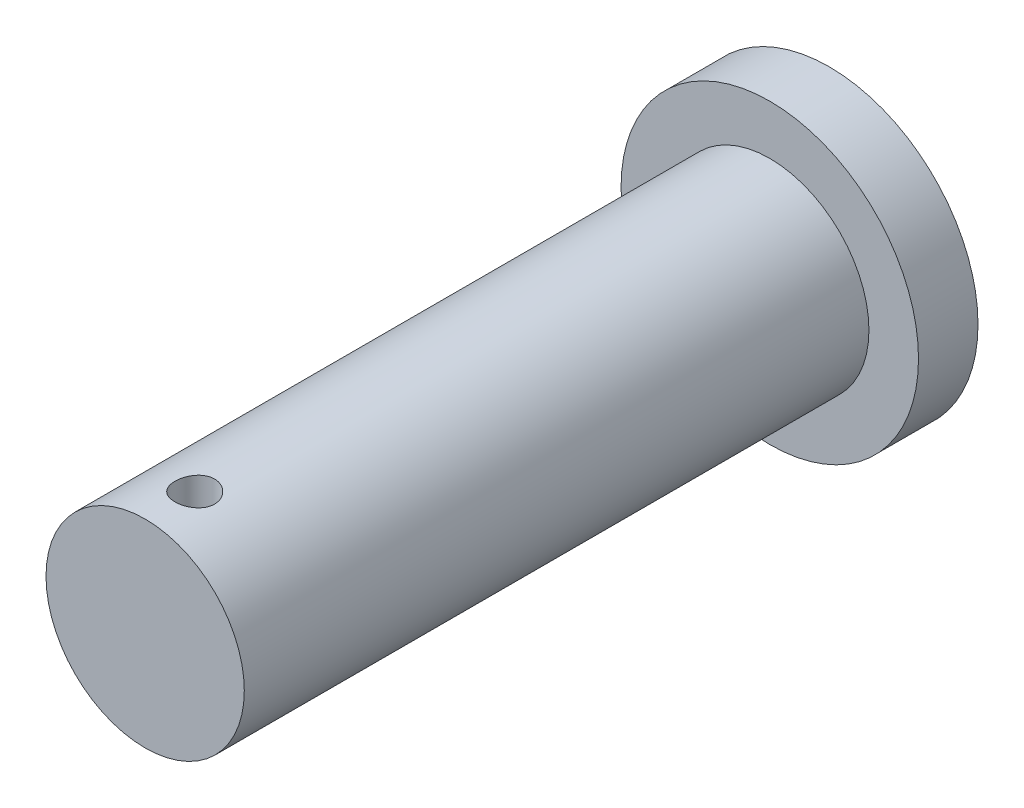
SolidWorks part; units mm, degrees
ref_plane "Front Plane" through (0, 0, 0) normal (0, 0, 1) x (1, 0, 0)
ref_plane "Top Plane" through (0, 0, 0) normal (0, 1, 0) x (1, 0, 0)
ref_plane "Right Plane" through (0, 0, 0) normal (1, 0, 0) x (0, 0, -1)
sketch "Sketch1" plane through (0, 0, 0) normal (0, 0, 1) x (1, 0, 0)
  circle A0 centre (0, 0) radius 5
  dimension "D1" = 10
extrude "Boss-Extrude1" add sketch "Sketch1" along normal blind 31.5
sketch "Sketch2" plane through (0, 0, 0) normal (0, 1, 0) x (1, 0, 0)
  line L0 (-5, -31.5) -> (5, -31.5) construction
  circle A0 centre (0, -29) radius 1
  dimension "D1" = 2
  dimension "D2" = 2.5
extrude "Cut-Extrude1" cut sketch "Sketch2" against normal mid plane 10
sketch "Sketch3" plane through (0, 0, 0) normal (0, 0, -1) x (-1, 0, 0)
  circle A0 centre (0, 0) radius 7.5
  dimension "D1" = 15
extrude "Boss-Extrude2" add sketch "Sketch3" along normal blind 3
equation "\"shaft inner diameter\"= 15mm "
equation "\"shaft outer diameter\"= 20mm "
equation "\"column angle\" = 45deg "
equation "\"keyway_height\" = 1.39mm "
equation "\"keyway_width\" = 2.78mm "
equation "\"keyway_length\" = 30mm "
equation "\"steering column length\" = 555mm "
equation "\"steering wheel bolt width\" = 6mm "
equation "\"steering wheel bolt length\" = 40mm "
equation "\"bushing length\" = 40mm "
equation "\"bushing thickness\" = 3mm "
equation "\"u_joint clearance\" = 30mm "
equation "\"u_joint thickness\" = 7.5mm "
equation "\"horizontal shaft length\" = 90mm "
equation "\"short_bearing_outer_width\" = 10mm "
equation "\"column bushing diameter\" = \"primary shaft small diameter\" + 4 "
equation "\"column bushing distance\" = \"steering column length\"/4 "
equation "\"pinion width\" = 26.5mm "
equation "\"pin hole diameter\" = 10mm "
equation "\"rack hole to hole\" = 500mm "
equation "\"rack length\" = \"rack hole to hole\" + \"pin hole diameter\"*2 "
equation "\"pitch diameter\" = \"max travel\"/(pi * \"turn to lock\") "
equation "\"number of teeth\" = 18mm "
equation "\"module\" = \"pitch diameter\" / \"number of teeth\" "
equation "\"pressure angle\" = 20deg "
equation "\"D1@Sketch1\"=\"pin hole diameter\""
equation "\"D1@Boss-Extrude1\"=\"pinion width\"+5mm"
equation "\"D1@Sketch3\"=\"pin hole diameter\"*1.5"
equation "\"wheel base\" = 1561mm "
equation "\"track\" = 1354mm "
equation "\"turning radius\" = 2000mm "
equation "\"steering arm length\" = 100mm "
equation "\"turn to lock\" = 0.75mm "
equation "\"max turning angle\" = atn(\"wheel base\" / (\"turning radius\" - 0.5 * \"track\")) "
equation "\"max travel\" = 2 * \"steering arm length\" * sin(0.5 * \"max turning angle\") "
equation "\"primary shaft small diameter\" = 16mm "
equation "\"primary shaft large diameter\" = 24mm "
equation "\"secondary shaft small diameter\" = 16mm "
equation "\"secondary shaft large diameter\" = 25mm "
equation "\"tie rod length\" = 305mm "
equation "\"tie rod inner diameter\" = 6.6mm "
equation "\"tie rod outer diameter\" = 8.1mm "
